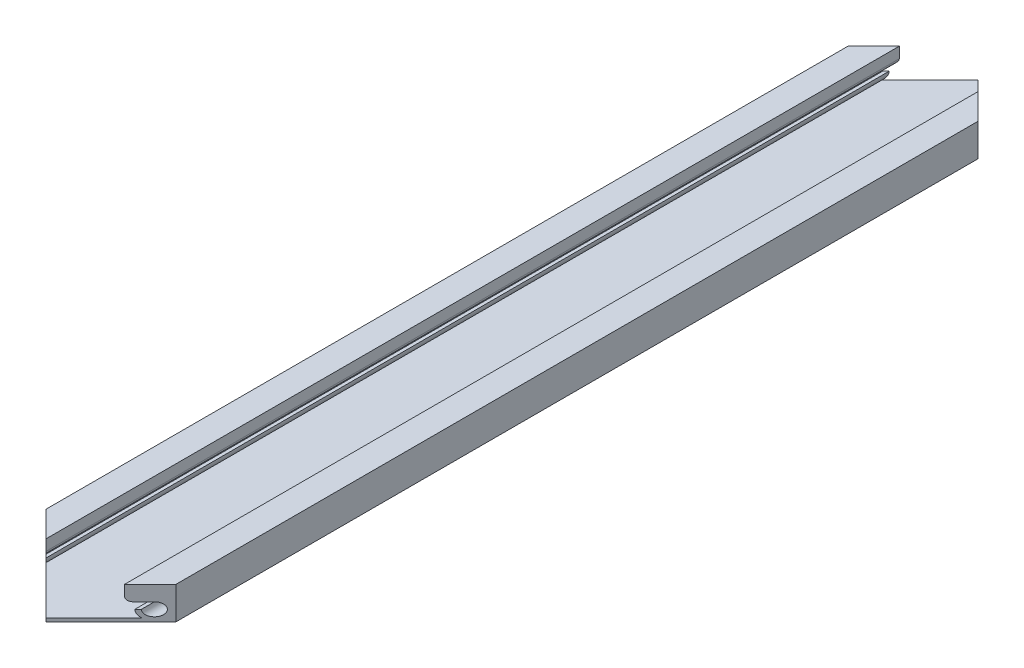
SolidWorks part; units mm, degrees
ref_plane "정면" through (0, 0, 0) normal (0, 0, 1) x (1, 0, 0)
ref_plane "윗면" through (0, 0, 0) normal (0, 1, 0) x (1, 0, 0)
ref_plane "우측면" through (0, 0, 0) normal (1, 0, 0) x (0, 0, -1)
sketch "스케치1" plane through (0, 0, 0) normal (0, 0, 1) x (1, 0, 0)
  line L1 (-30, 7.5) -> (30, 7.5)
  line L2 (-30, 7.5) -> (-30, -7.5)
  line L3 (-30, -7.5) -> (30, -7.5)
  line L4 (30, 7.5) -> (30, -7.5)
  line L5 (-30, 7.5) -> (30, -7.5) construction
  line L6 (-30, -7.5) -> (30, 7.5) construction
  point P0 (0, 0)
  dimension "D1" = 60
  dimension "D2" = 15
extrude "보스-돌출1" add sketch "스케치1" along normal blind 430
sketch "스케치2" plane through (0, 0, 0) normal (0, 0, -1) x (-1, 0, 0)
  line L0 (30, -7.5) -> (-30, -7.5) construction
  line L2 (-30, -7.5) -> (-30, 7.5) construction
  line L3 (30, 7.5) -> (30, -7.5) construction
  circle A0 centre (-25, -2.5) radius 3
  circle A1 centre (25, -2.5) radius 3
  point P8 (-30, -0.62)
  dimension "D1" = 6
  dimension "D3" = 5
  dimension "D4" = 6
  dimension "D6" = 5
  dimension "D2" = 5
  dimension "D5" = 5
extrude "컷-돌출1" cut sketch "스케치2" against normal through all
sketch "스케치3" plane through (0, 0, 0) normal (0, 0, -1) x (-1, 0, 0)
  line L0 (-22.1716, -6) -> (22.1716, -6)
  line L1 (-20.5, -2.5) -> (-25, -2.5)
  line L2 (-25, -2.5) -> (-25, 0.5)
  line L3 (-25, 0.5) -> (25, 0.5)
  line L4 (25, 0.5) -> (25, -2.5)
  line L5 (25, -2.5) -> (20.5, -2.5)
  line L6 (30, -7.5) -> (-30, -7.5) construction
  arc A0 (22.1716, -6) -> (20.5, -2.5) centre (25, -2.5) cw
  arc A1 (-22.1716, -6) -> (-20.5, -2.5) centre (-25, -2.5) ccw
  circle A2 centre (-25, -2.5) radius 3 construction
  circle A3 centre (25, -2.5) radius 3 construction
  point P16 (0, 0)
  point P17 (-25, 1.6205)
  dimension "D2" = 1.5
  dimension "D1" = 1.5
  dimension "1.5" = 1.5
extrude "컷-돌출2" cut sketch "스케치3" against normal through all
sketch "스케치4" plane through (0, 0, 0) normal (0, 0, -1) x (-1, 0, 0)
  line L0 (-18.1431, 0.5) -> (18.1569, 0.5)
  line L1 (25, 0.5) -> (-25, 0.5) construction
  line L2 (-18.1431, 0.5) -> (-18.1431, 7.5)
  line L3 (-30, 7.5) -> (30, 7.5) construction
  line L4 (-18.1431, 7.5) -> (18.1569, 7.5)
  line L5 (18.1569, 7.5) -> (18.1569, 0.5)
  point P5 (0, 0)
  dimension "D1" = 36.3
extrude "컷-돌출3" cut sketch "스케치4" against normal through all
fillet "필렛1" radius 2 2 edges at (-18.1569, 0.5, 215) (18.1431, 0.5, 215)
sketch "스케치5" plane through (0, -7.5, 0) normal (0, -1, 0) x (1, 0, 0)
  line L0 (-30, 430) -> (-30, 400)
  line L1 (-30, 430) -> (-30, 0) construction
  line L2 (-30, 400) -> (0, 430)
  line L3 (-30, 430) -> (30, 430) construction
  line L4 (30, 430) -> (-30, 430)
  line L5 (0, 442.8165) -> (0, -66.3343) construction
  line L6 (-30, 215) -> (30, 215) construction
  line L7 (30, 430) -> (30, 0) construction
  line L8 (30, 400) -> (0, 430)
  line L9 (30, 430) -> (30, 400)
  line L10 (30, 0) -> (30, 30)
  line L11 (30, 30) -> (0, 0)
  line L12 (30, 0) -> (-30, 0)
  line L13 (-30, 30) -> (0, 0)
  line L14 (-30, 0) -> (-30, 30)
  line M8 (-30, 0) -> (30, 0)
  line M9 (30, 0) -> (30, 430)
  line M10 (30, 430) -> (-30, 430)
  line M11 (-30, 430) -> (-30, 0)
  dimension "D1" = 45
extrude "컷-돌출4" cut sketch "스케치5" against normal through all contours L8 M9 M10 | L2 M11 M10 | L13 M11 M8 | L11 M9 M8
